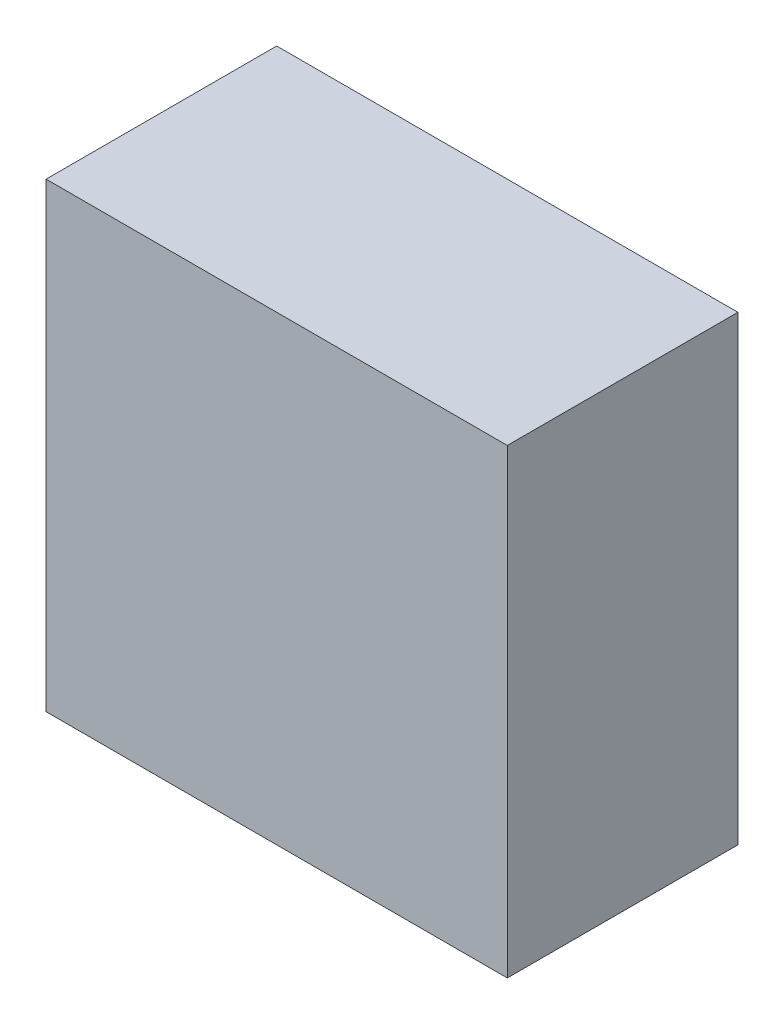
SolidWorks part; units mm, degrees
ref_plane "Plan de face" through (0, 0, 0) normal (0, 0, 1) x (1, 0, 0)
ref_plane "Plan de dessus" through (0, 0, 0) normal (0, 1, 0) x (1, 0, 0)
ref_plane "Plan de droite" through (0, 0, 0) normal (1, 0, 0) x (0, 0, -1)
sketch "Esquisse1" plane through (0, 0, 0) normal (0, 0, 1) x (1, 0, 0)
  line L1 (-5, -5) -> (5, -5)
  line L2 (-5, -5) -> (-5, 5)
  line L3 (-5, 5) -> (5, 5)
  line L4 (5, -5) -> (5, 5)
  line L5 (-5, -5) -> (5, 5) construction
  line L6 (-5, 5) -> (5, -5) construction
  point P0 (0, 0)
  dimension "D1" = 10
  dimension "D2" = 10
extrude "Extrusion1" add sketch "Esquisse1" along normal blind 5
